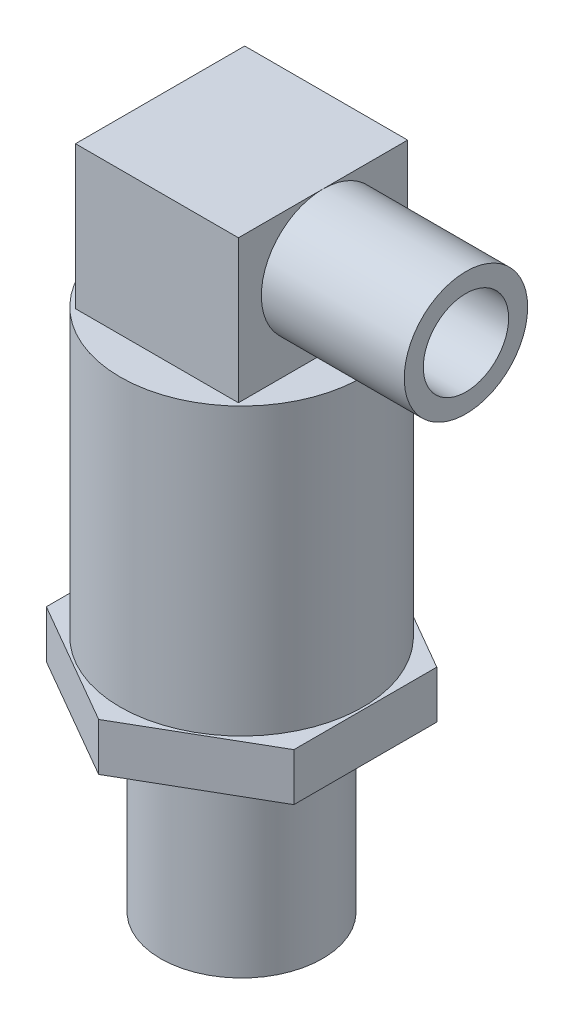
SolidWorks part; units mm, degrees
material "AISI 316  (SS)"
ref_plane "Front" through (0, 0, 0) normal (0, 0, 1) x (1, 0, 0)
ref_plane "Top" through (0, 0, 0) normal (0, 1, 0) x (1, 0, 0)
ref_plane "Right" through (0, 0, 0) normal (1, 0, 0) x (0, 0, -1)
sketch "Sketch1" plane through (0, 0, 0) normal (0, 1, 0) x (1, 0, 0)
  circle A0 centre (0, 0) radius 8.5
  dimension "D1" = 17
extrude "Boss-Extrude1" add sketch "Sketch1" against normal blind 20
sketch "Sketch2" plane through (0, 0, 0) normal (0, 1, 0) x (1, 0, 0)
  line L1 (0, 15) -> (-12.9904, 7.5)
  line L2 (-12.9904, 7.5) -> (-12.9904, -7.5)
  line L3 (-12.9904, -7.5) -> (0, -15)
  line L4 (0, -15) -> (12.9904, -7.5)
  line L5 (12.9904, -7.5) -> (12.9904, 7.5)
  line L6 (12.9904, 7.5) -> (0, 15)
  circle A0 centre (0, 0) radius 12.9904 construction
  dimension "D1" = 15
extrude "Boss-Extrude2" add sketch "Sketch2" along normal blind 5
sketch "Sketch3" plane through (0, 5, 0) normal (0, 1, 0) x (1, 0, 0)
  circle A0 centre (0, 0) radius 12.7493
extrude "Boss-Extrude3" add sketch "Sketch3" along normal blind 30
sketch "Sketch4" plane through (0, 35, 0) normal (0, 1, 0) x (1, 0, 0)
  line L1 (-8.5512, -8.8814) -> (8.5512, -8.8814)
  line L2 (-8.5512, -8.8814) -> (-8.5512, 8.8814)
  line L3 (-8.5512, 8.8814) -> (8.5512, 8.8814)
  line L4 (8.5512, -8.8814) -> (8.5512, 8.8814)
  line L5 (-8.5512, -8.8814) -> (8.5512, 8.8814) construction
  line L6 (-8.5512, 8.8814) -> (8.5512, -8.8814) construction
  point P0 (0, 0)
extrude "Boss-Extrude4" add sketch "Sketch4" along normal blind 15
sketch "Sketch5" plane through (8.5512, 0, 0) normal (1, 0, 0) x (0, 0, -1)
  circle A0 centre (0, 43.5226) radius 6.4774
extrude "Extrude-Thin1" add sketch "Sketch5" along normal blind 15 thin thin type one direction reverse wall 2
